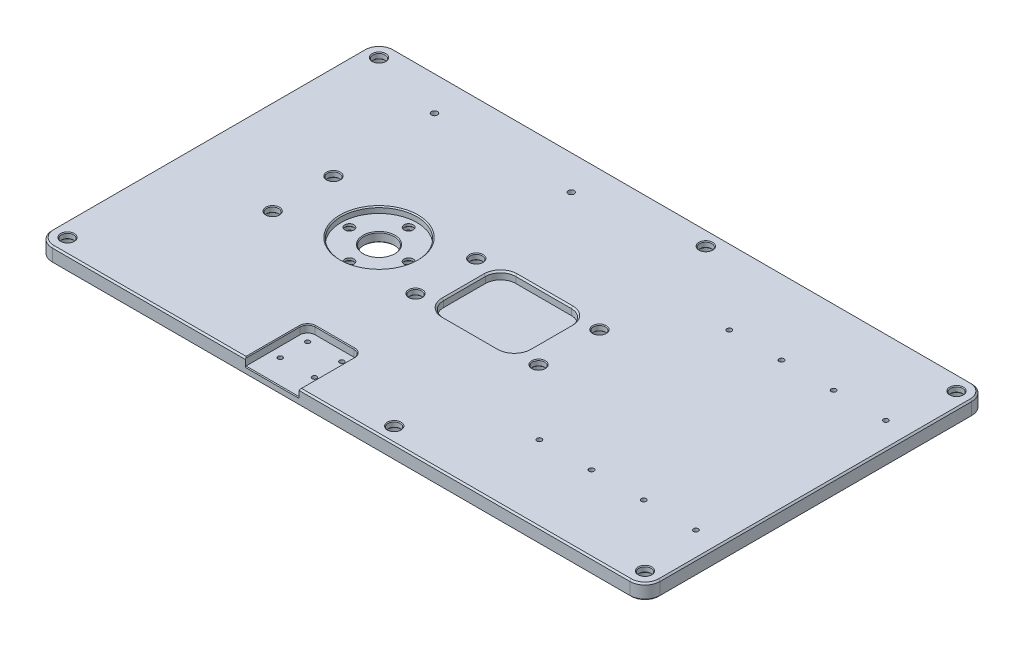
SolidWorks part; units mm, degrees
material "AISI 1020"
ref_plane "Přední rovina" through (0, 0, 0) normal (0, 0, 1) x (1, 0, 0)
ref_plane "Horní rovina" through (0, 0, 0) normal (0, 1, 0) x (1, 0, 0)
ref_plane "Pravá rovina" through (0, 0, 0) normal (1, 0, 0) x (0, 0, -1)
sketch "Skica2" plane through (0, 0, 0) normal (0, 1, 0) x (1, 0, 0)
  line L1 (0, 0) -> (400, 0)
  line L2 (0, 0) -> (0, 225)
  line L3 (0, 225) -> (400, 225)
  line L4 (400, 0) -> (400, 225)
  line L5 (0, 0) -> (400, 225) construction
  line L6 (0, 225) -> (400, 0) construction
  point P4 (200, 112.5)
  dimension "D1" = 225
  dimension "D2" = 400
extrude "Přidat vysunutím1" add sketch "Skica2" along normal blind 10
sketch "Skica3" plane through (0, 10, 0) normal (0, 1, 0) x (1, 0, 0)
  line L0 (0, 112.5) -> (400, 112.5) construction
  line L1 (0, 225) -> (0, 0) construction
  line L2 (400, 0) -> (400, 225) construction
  line L5 (62.5, 92.5) -> (342.5, 92.5) construction
  line L6 (62.5, 92.5) -> (62.5, 132.5) construction
  line L7 (62.5, 132.5) -> (342.5, 132.5) construction
  line L8 (342.5, 92.5) -> (342.5, 132.5) construction
  line L9 (62.5, 92.5) -> (342.5, 132.5) construction
  line L10 (62.5, 132.5) -> (342.5, 92.5) construction
  circle A0 centre (62.5, 92.5) radius 10 construction
  circle A1 centre (62.5, 92.5) radius 4
  circle A2 centre (62.5, 132.5) radius 4
  circle A5 centre (156.5, 92.5) radius 4
  circle A6 centre (156.5, 132.5) radius 4
  circle A7 centre (237.5, 92.5) radius 4
  circle A8 centre (237.5, 132.5) radius 4
  circle A9 centre (112.5, 112.5) radius 10
  point P14 (202.5, 112.5)
  dimension "D1" = 20
  dimension "D4" = 8
  dimension "D5" = 8
  dimension "D10" = 58.5
  dimension "D11" = 8
  dimension "D12" = 8
  dimension "D14" = 8
  dimension "D15" = 8
  dimension "D17" = 112.5
  dimension "D18" = 20
  dimension "D2" = 62.5
  dimension "D3" = 40
  dimension "D13" = 94
  dimension "D16" = 81
extrude "Odebrat vysunutím1" cut sketch "Skica3" against normal blind 10
sketch "Skica4" plane through (0, 0, 0) normal (0, -1, 0) x (1, 0, 0)
  circle A0 centre (62.5, -92.5) radius 7.5
  circle A1 centre (62.5, -132.5) radius 7
  circle A2 centre (156.5, -92.5) radius 7.5
  circle A3 centre (156.5, -132.5) radius 7.5
  circle A4 centre (237.5, -92.5) radius 7.5
  circle A5 centre (237.5, -132.5) radius 7.5
  dimension "D1" = 15
  dimension "D2" = 15
  dimension "D3" = 15
  dimension "D5" = 14
  dimension "D6" = 15
  dimension "D7" = 15
extrude "Odebrat vysunutím2" cut sketch "Skica4" against normal blind 6
fillet "Zaoblit1" radius 10 4 edges at (400, 5, -225) (400, 5, 0) (0, 5, 0) (0, 5, -225)
sketch "Skica6" plane through (0, 0, 0) normal (0, -1, 0) x (1, 0, 0)
  line L0 (225, -10) -> (225, -215) construction
  circle A0 centre (10, -10) radius 4
  circle A1 centre (390, -10) radius 4
  circle A2 centre (390, -215) radius 4
  circle A3 centre (10, -215) radius 4
  circle A4 centre (225, -10) radius 4
  circle A5 centre (225, -215) radius 4
  dimension "D1" = 8
  dimension "D2" = 8
  dimension "D4" = 8
  dimension "D5" = 8
  dimension "D6" = 215
  dimension "D3" = 2
extrude "Odebrat vysunutím4" cut sketch "Skica6" against normal up to surface (10 mm away) up to face at (62.5, 10, -88.5)
sketch "Skica7" plane through (0, 0, 0) normal (0, -1, 0) x (1, 0, 0)
  circle A0 centre (10, -10) radius 7.5
  circle A1 centre (390, -10) radius 7.5
  circle A2 centre (10, -215) radius 7.5
  circle A3 centre (390, -215) radius 7.5
  circle A4 centre (225, -10) radius 7.5
  circle A5 centre (225, -215) radius 7.5
  dimension "D1" = 15
  dimension "D2" = 15
  dimension "D4" = 15
  dimension "D5" = 15
  dimension "D3" = 2
extrude "Odebrat vysunutím5" cut sketch "Skica7" against normal blind 6
chamfer "Zkosení1" distance 0.5 angle 45 18 edges at (62.5, 10, -128.5) (62.5, 10, -88.5) (156.5, 10, -88.5) (156.5, 10, -128.5) (237.5, 10, -128.5) (237.5, 10, -88.5) (237.5, 0, -140) (237.5, 6, -136.5) (237.5, 0, -100) (237.5, 6, -96.5) (156.5, 0, -140) (156.5, 6, -136.5) (156.5, 0, -100) (156.5, 6, -96.5) (62.5, 0, -139.5) (62.5, 6, -136.5) (62.5, 0, -100) (62.5, 6, -96.5)
chamfer "Zkosení2" distance 0.5 angle 45 18 edges at (10, 6, -14) (10, 10, -14) (10, 6, -219) (10, 10, -219) (225, 6, -219) (225, 10, -219) (390, 6, -219) (390, 10, -219) (390, 6, -14) (390, 10, -14) (225, 6, -14) (225, 10, -14) (10, 0, -17.5) (10, 0, -222.5) (225, 0, -222.5) (390, 0, -222.5) (390, 0, -17.5) (225, 0, -17.5)
chamfer "Zkosení3" distance 0.5 angle 45 2 edges at (112.5, 0, -102.5) (112.5, 10, -102.5)
chamfer "Zkosení5" distance 1 angle 45 16 edges at (200, 0, -225) (2.9289, 0, -222.0711) (397.0711, 0, -222.0711) (0, 0, -112.5) (400, 0, -112.5) (2.9289, 0, -2.9289) (397.0711, 0, -2.9289) (200, 0, 0) (200, 10, -225) (2.9289, 10, -222.0711) (397.0711, 10, -222.0711) (0, 10, -112.5) (400, 10, -112.5) (2.9289, 10, -2.9289) (397.0711, 10, -2.9289) (200, 10, 0)
sketch "Skica8" plane through (0, 10, 0) normal (0, 1, 0) x (1, 0, 0)
  circle A0 centre (112.5, 112.5) radius 25
  dimension "D1" = 50
extrude "Odebrat vysunutím6" cut sketch "Skica8" against normal blind 4
sketch "Skica10" plane through (0, 6, 0) normal (0, 1, 0) x (1, 0, 0)
  circle A0 centre (112.5, 112.5) radius 19.5 construction
  circle A1 centre (112.5, 132) radius 3
  circle A2 centre (132, 112.5) radius 3
  circle A3 centre (112.5, 93) radius 3
  circle A4 centre (93, 112.5) radius 3
  point P14 (112.5, 112.5)
  dimension "D1" = 39
  dimension "D2" = 6
  dimension "D3" = 4
extrude "Odebrat vysunutím7" cut sketch "Skica10" against normal up to surface (6 mm away) up to face at (200, 0, -112.5)
sketch "Skica11" plane through (0, 0, 0) normal (0, -1, 0) x (1, 0, 0)
  circle A0 centre (112.5, -93) radius 5.5
  circle A1 centre (132, -112.5) radius 5.5
  circle A2 centre (112.5, -132) radius 5.5
  circle A3 centre (93, -112.5) radius 5.5
  point P12 (112.5, -112.5)
  dimension "D1" = 11
  dimension "D2" = 4
extrude "Odebrat vysunutím8" cut sketch "Skica11" against normal blind 4
chamfer "Zkosení7" distance 0.5 angle 45 1 edges at (112.5, 6, -102.5)
sketch "Skica12" plane through (0, 10, 0) normal (0, 1, 0) x (1, 0, 0)
  line L0 (383.49, 50) -> (280.5, 50) construction
  line L1 (390, 0) -> (10, 0) construction
  line L3 (399, 112.5) -> (0, 112.5) construction
  line L4 (399, 10) -> (399, 215) construction
  line L5 (0, 10) -> (0, 215) construction
  line L6 (383.49, 175) -> (280.5, 175) construction
  line L7 (237.5, 92.5) -> (237.5, 0) construction
  circle A0 centre (383.49, 50) radius 1.6
  circle A1 centre (349.16, 50) radius 1.6
  circle A2 centre (314.83, 50) radius 1.6
  circle A3 centre (280.5, 50) radius 1.6
  circle A4 centre (280.5, 175) radius 1.6
  circle A5 centre (314.83, 175) radius 1.6
  circle A6 centre (349.16, 175) radius 1.6
  circle A7 centre (383.49, 175) radius 1.6
  dimension "D1" = 3.2
  dimension "D4" = 34.33
  dimension "D7" = 3.2
  dimension "D8" = 3.2
  dimension "D9" = 3.2
  dimension "D2" = 50
  dimension "D3" = 43
  dimension "D5" = 34.33
  dimension "D6" = 34.33
extrude "Odebrat vysunutím9" cut sketch "Skica12" against normal up to surface (10 mm away) up to face at (112.5, 0, -98.5)
cosmetic thread "Kosmetický závit1" parameters "D2"=4
cosmetic thread "Kosmetický závit2" parameters "D2"=4
cosmetic thread "Kosmetický závit3" parameters "D2"=4
cosmetic thread "Kosmetický závit4" parameters "D2"=4
cosmetic thread "Kosmetický závit5" parameters "D2"=4
cosmetic thread "Kosmetický závit6" parameters "D2"=4
cosmetic thread "Kosmetický závit7" parameters "D2"=4
cosmetic thread "Kosmetický závit8" parameters "D2"=4
sketch "Skica13" plane through (0, 10, 0) normal (0, 1, 0) x (1, 0, 0)
  line L0 (10, 1) -> (390, 1) construction
  line L4 (142, 41) -> (167.5, 41)
  line L7 (137, 36) -> (137, -17.5247)
  line L8 (137, -17.5247) -> (172.5, -17.5247)
  line L9 (172.5, 36) -> (172.5, -17.5247)
  line L10 (137, 41) -> (172.5, -17.5247) construction
  line L11 (137, -17.5247) -> (172.5, 41) construction
  arc A5 (167.5, 41) -> (172.5, 36) centre (167.5, 36) cw
  arc A6 (142, 41) -> (137, 36) centre (142, 36) ccw
  circle A7 centre (225, 10) radius 4.5 construction
  point P4 (154.75, 11.7377)
  dimension "D3" = 5
  dimension "D1" = 40
  dimension "D2" = 35.5
  dimension "D4" = 52.5
extrude "Odebrat vysunutím10" cut sketch "Skica13" against normal blind 5
sketch "Skica14" plane through (0, 5, 0) normal (0, 1, 0) x (1, 0, 0)
  line L0 (154.75, 41) -> (154.75, 0) construction
  line L1 (167.5, 41) -> (142, 41) construction
  line L2 (137, 0) -> (172.5, 0) construction
  line L3 (167.5, 41) -> (142, 41) construction
  line L4 (143.5, 16.5) -> (166, 16.5) construction
  line L5 (143.5, 16.5) -> (143.5, 34.5) construction
  line L6 (143.5, 34.5) -> (166, 34.5) construction
  line L7 (166, 16.5) -> (166, 34.5) construction
  line L8 (143.5, 16.5) -> (166, 34.5) construction
  line L9 (143.5, 34.5) -> (166, 16.5) construction
  circle A0 centre (143.5, 34.5) radius 1.5
  circle A4 centre (166, 34.5) radius 1.5
  circle A5 centre (166, 16.5) radius 1.5
  circle A6 centre (143.5, 16.5) radius 1.5
  point P6 (154.75, 25.5)
  dimension "D1" = 3
  dimension "D5" = 2
  dimension "D2" = 22.5
  dimension "D3" = 18
  dimension "D4" = 6.5
extrude "Odebrat vysunutím11" cut sketch "Skica14" against normal up to surface (5 mm away) up to face at (349.16, 0, -51.6)
cosmetic thread "Kosmetický závit9" parameters "D2"=4
cosmetic thread "Kosmetický závit10" parameters "D2"=4
cosmetic thread "Kosmetický závit11" parameters "D2"=4
cosmetic thread "Kosmetický závit12" parameters "D2"=4
sketch "Skica15" plane through (0, 10, 0) normal (0, 1, 0) x (1, 0, 0)
  line L0 (0, 112.5) -> (400, 112.5) construction
  line L1 (0, 10) -> (0, 215) construction
  line L2 (400, 215) -> (400, 10) construction
  line L4 (225.25, 88.75) -> (168.75, 88.75)
  line L5 (225.25, 88.75) -> (225.25, 136.25)
  line L6 (225.25, 136.25) -> (168.75, 136.25)
  line L7 (168.75, 88.75) -> (168.75, 136.25)
  line L8 (225.25, 88.75) -> (168.75, 136.25) construction
  line L9 (225.25, 136.25) -> (168.75, 88.75) construction
  circle A0 centre (112.5, 112.5) radius 10 construction
  point P6 (197, 112.5)
  dimension "D1" = 56.5
  dimension "D2" = 47.5
  dimension "D3" = 56.25
extrude "Odebrat vysunutím12" cut sketch "Skica15" against normal blind 5
fillet "Zaoblit2" radius 10 4 edges at (225.25, 7.5, -88.75) (168.75, 7.5, -88.75) (225.25, 7.5, -136.25) (168.75, 7.5, -136.25)
sketch "Skica16" plane through (0, 0, 0) normal (0, -1, 0) x (1, 0, 0)
  line L0 (0, -201.5) -> (195.4662, -201.5) construction
  line L1 (0, -215) -> (0, -10) construction
  line L2 (390, -225) -> (10, -225) construction
  circle A0 centre (60, -201.5) radius 2
  circle A1 centre (150, -201.5) radius 2
  dimension "D1" = 90
  dimension "D4" = 4
  dimension "D5" = 4
  dimension "D2" = 23.5
  dimension "D3" = 60
extrude "Odebrat vysunutím13" cut sketch "Skica16" against normal up to surface (10 mm away) up to face at (197, 10, -112.5)
sketch "Skica17" plane through (0, 0, 0) normal (0, -1, 0) x (1, 0, 0)
  circle A0 centre (60, -201.5) radius 4
  circle A1 centre (150, -201.5) radius 4
  dimension "D1" = 8
  dimension "D2" = 8
extrude "Odebrat vysunutím14" cut sketch "Skica17" against normal blind 4
chamfer "Zkosení8" distance 0.5 angle 45 4 edges at (150, 4, -203.5) (60, 4, -203.5) (150, 0, -205.5) (60, 0, -205.5)
chamfer "Zkosení9" distance 0.5 angle 45 8 edges at (132, 0, -118) (112.5, 0, -98.5) (93, 0, -118) (112.5, 0, -137.5) (112.5, 4, -135) (132, 4, -115.5) (112.5, 4, -96) (93, 4, -115.5)
chamfer "Zkosení10" distance 0.7 angle 45 1 edges at (112.5, 10, -87.5)
chamfer "Zkosení11" distance 1 angle 45 8 edges at (197, 10, -88.75) (222.3211, 10, -91.6789) (171.6789, 10, -91.6789) (225.25, 10, -112.5) (168.75, 10, -112.5) (222.3211, 10, -133.3211) (171.6789, 10, -133.3211) (197, 10, -136.25)
chamfer "Zkosení12" distance 0.5 angle 45 5 edges at (172.5, 10, -18.5) (137, 10, -18.5) (171.0355, 10, -39.5355) (138.4645, 10, -39.5355) (154.75, 10, -41)
chamfer "Zkosení13" distance 0.5 angle 45 1 edges at (154.75, 5, 0)
equation "\"¨10\"=12.8271"
